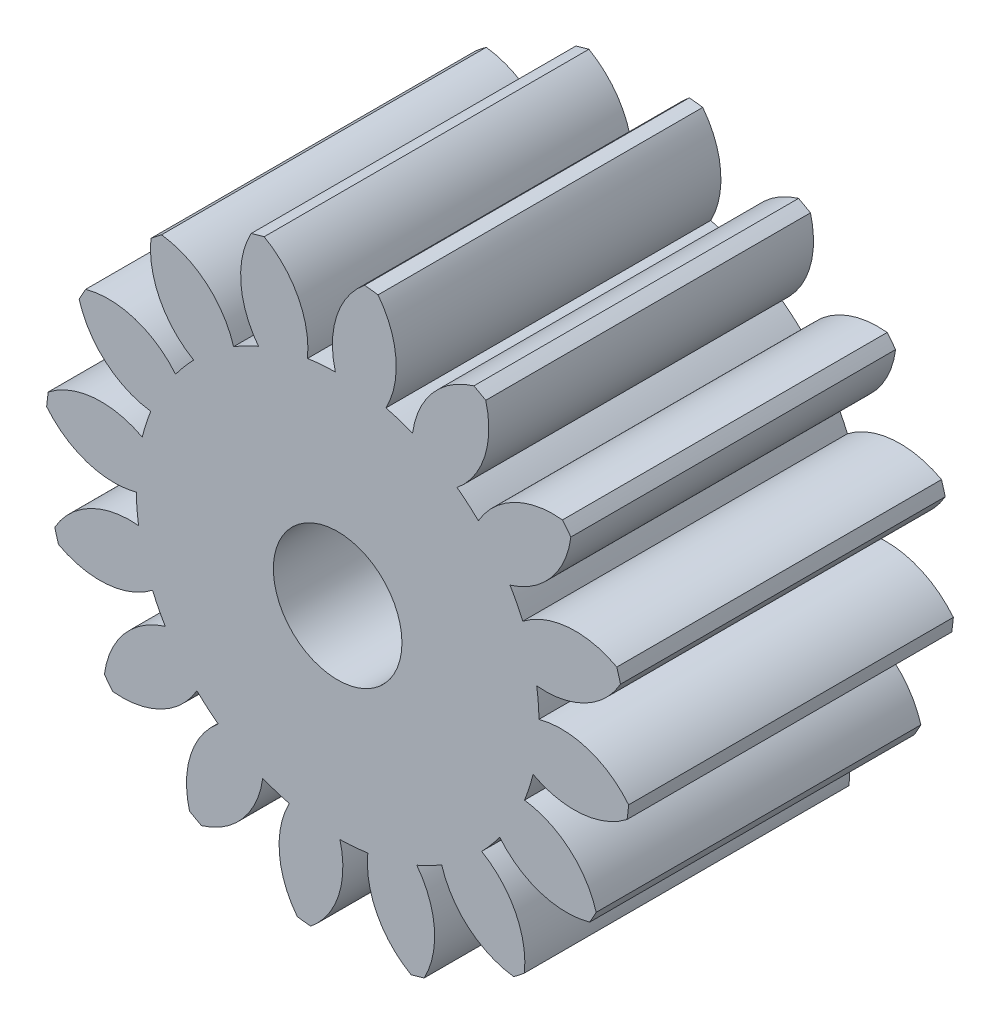
SolidWorks part; units mm, degrees
ref_plane "Alzado" through (0, 0, 0) normal (0, 0, 1) x (1, 0, 0)
ref_plane "Planta" through (0, 0, 0) normal (0, 1, 0) x (1, 0, 0)
ref_plane "Vista lateral" through (0, 0, 0) normal (1, 0, 0) x (0, 0, -1)
sketch "Croquis1" plane through (0, 0, 0) normal (0, 0, 1) x (1, 0, 0)
  circle A0 centre (0, 0) radius 4.5
  circle A1 centre (0, 0) radius 0.99
  dimension "D1" = 9
  dimension "D2" = 1.98
extrude "Saliente-Extruir1" add sketch "Croquis1" along normal blind 5
sketch "Croquis2" plane through (0, 0, 5) normal (0, 0, 1) x (1, 0, 0)
  line L0 (0, 0) -> (0, 6.1678) construction
  line L1 (0, 0) -> (1.8072, 4.9651) construction
  line L2 (0, 3.9) -> (1.2534, 3.4438) construction
  line L3 (0, 0) -> (-0.5, 6.1678) construction
  circle A0 centre (0, 0) radius 4.5
  circle A1 centre (0, 0) radius 3.1
  circle A2 centre (0, 0) radius 3.9
  arc A3 (0.4146, 4.4809) -> (-0.0353, 3.0998) centre (1.2534, 3.4438) ccw
  arc A4 (-1.1309, 4.3556) -> (-0.4644, 3.065) centre (-1.7918, 3.1969) cw
  circle M9 centre (0, 0) radius 4.5
  dimension "D1" = 6.2
  dimension "D2" = 7.8
  dimension "D5" = 9
  dimension "D3" = 20
  dimension "D4" = 0.5
extrude "Cortar-Extruir1" cut sketch "Croquis2" against normal blind 5 contours A4 A2 A3 M9 | A2 A4 A1 A3
pattern_circular "MatrizC1" count 16 over 360 about axis through (0, 0, 0) along (0, 0, 1) of "Cortar-Extruir1"
